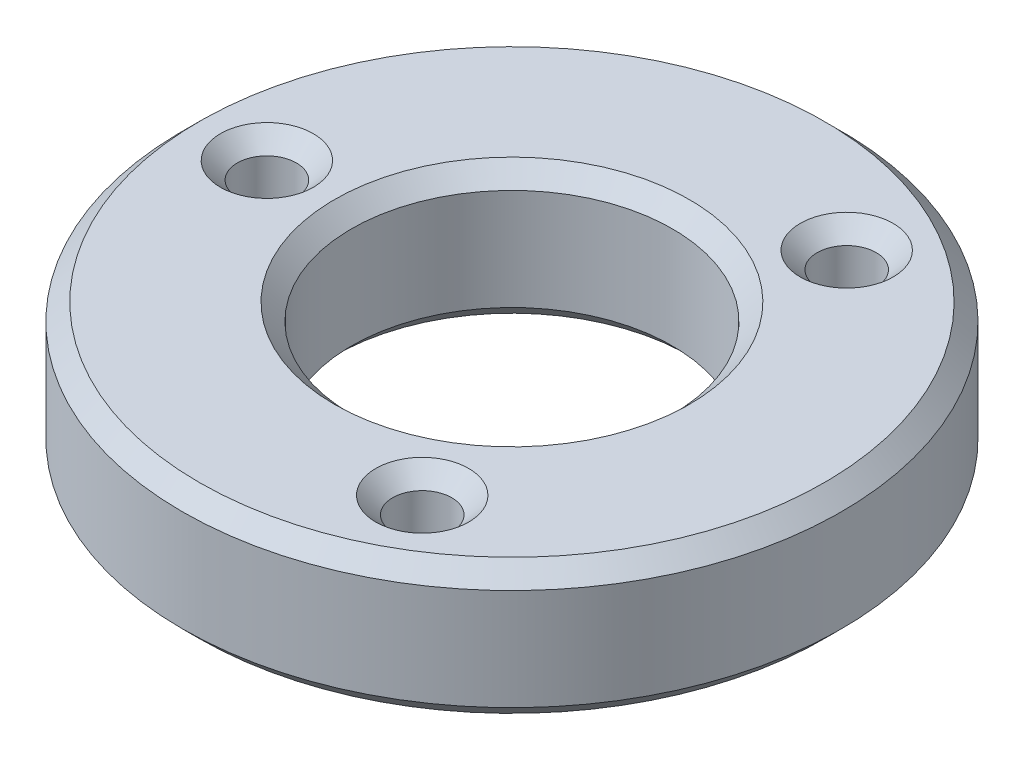
SolidWorks part; units mm, degrees
ref_plane "Front Plane" through (0, 0, 0) normal (0, 0, 1) x (1, 0, 0)
ref_plane "Top Plane" through (0, 0, 0) normal (0, 1, 0) x (1, 0, 0)
ref_plane "Right Plane" through (0, 0, 0) normal (1, 0, 0) x (0, 0, -1)
sketch "Sketch1" plane through (0, 0, 0) normal (0, 1, 0) x (1, 0, 0)
  line L0 (-24.9372, 0) -> (38.3859, 0) construction
  circle A0 centre (0, 0) radius 9.5
  circle A1 centre (0, 0) radius 19.5
  circle A2 centre (-14.5, 0) radius 1.75
  circle A3 centre (7.25, 12.5574) radius 1.75
  circle A4 centre (7.25, -12.5574) radius 1.75
  point P15 (0, 0)
  dimension "D1" = 39
  dimension "D2" = 19
  dimension "D3" = 3.5
  dimension "D4" = 14.5
  dimension "D6" = 12.5574
  dimension "D7" = 12.5574
  dimension "D5" = 3
extrude "Boss-Extrude1" add sketch "Sketch1" along normal blind 8
chamfer "Chamfer1" distance 1 angle 45 10 edges at (7.25, 0, 14.3074) (7.25, 0, -10.8074) (-14.5, 0, 1.75) (0, 0, 9.5) (0, 0, 19.5) (7.25, 8, 14.3074) (-14.5, 8, 1.75) (0, 8, 19.5) (0, 8, 9.5) (7.25, 8, -10.8074)
